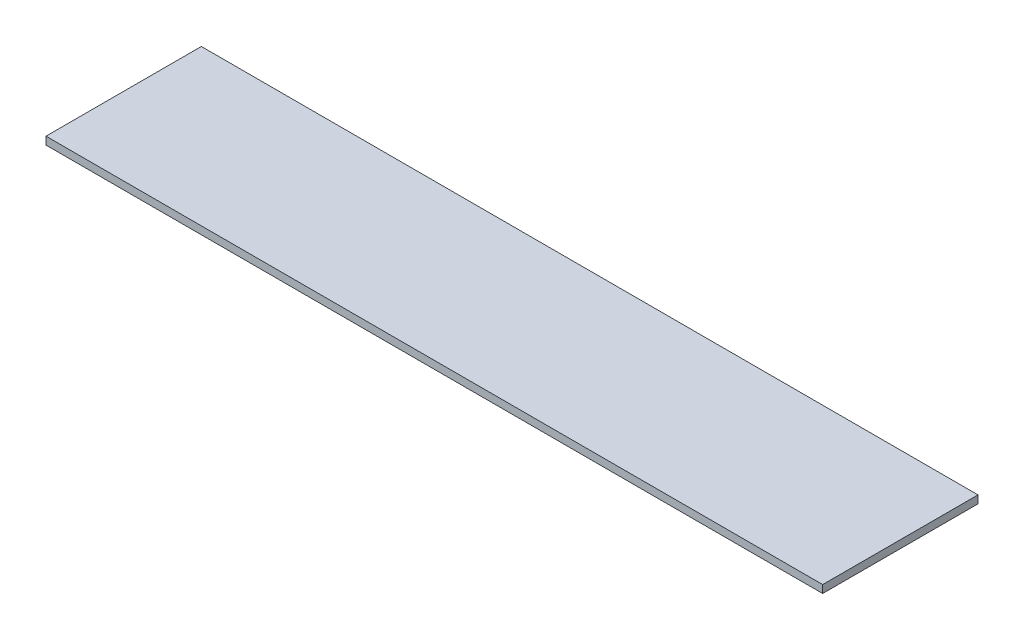
SolidWorks part; units mm, degrees
material "Acrylic (Medium-high impact)"
ref_plane "Front Plane" through (0, 0, 0) normal (0, 0, 1) x (1, 0, 0)
ref_plane "Top Plane" through (0, 0, 0) normal (0, 1, 0) x (1, 0, 0)
ref_plane "Right Plane" through (0, 0, 0) normal (1, 0, 0) x (0, 0, -1)
sketch "Sketch1" plane through (0, 0, 0) normal (0, 1, 0) x (1, 0, 0)
  line L1 (-242.5312, 876.0133) -> (4837.4688, 876.0133)
  line L2 (-242.5312, 876.0133) -> (-242.5312, -139.9867)
  line L3 (-242.5312, -139.9867) -> (4837.4688, -139.9867)
  line L4 (4837.4688, 876.0133) -> (4837.4688, -139.9867)
  dimension "D1" = 5080
  dimension "D2" = 1016
extrude "Boss-Extrude1" add sketch "Sketch1" along normal blind 50.8
